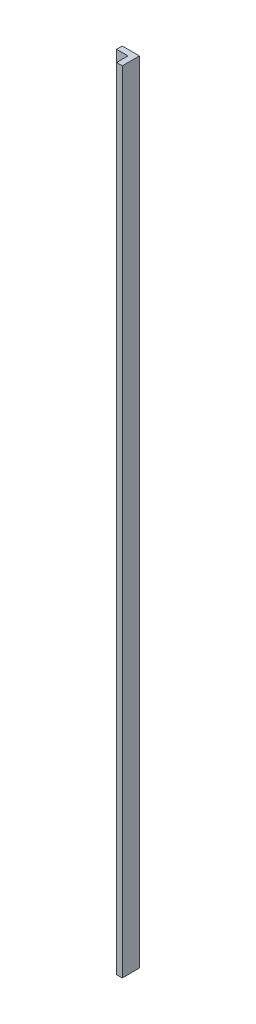
SolidWorks part; units mm, degrees
ref_plane "Front Plane" through (0, 0, 0) normal (0, 0, 1) x (1, 0, 0)
ref_plane "Top Plane" through (0, 0, 0) normal (0, 1, 0) x (1, 0, 0)
ref_plane "Right Plane" through (0, 0, 0) normal (1, 0, 0) x (0, 0, -1)
sketch "Sketch1" plane through (0, 0, 0) normal (0, 1, 0) x (1, 0, 0)
  line L0 (0, 0) -> (-30, 0)
  line L5 (0, 0) -> (0, -30)
  line L6 (0, -30) -> (-10, -30)
  line L7 (-10, -30) -> (-10, -10)
  line L8 (-10, -10) -> (-30, -10)
  line L9 (-30, -10) -> (-30, 0)
  dimension "D1" = 30
  dimension "D2" = 30
  dimension "D3" = 10
  dimension "D4" = 10
extrude "Boss-Extrude1" add sketch "Sketch1" along normal blind 1380
